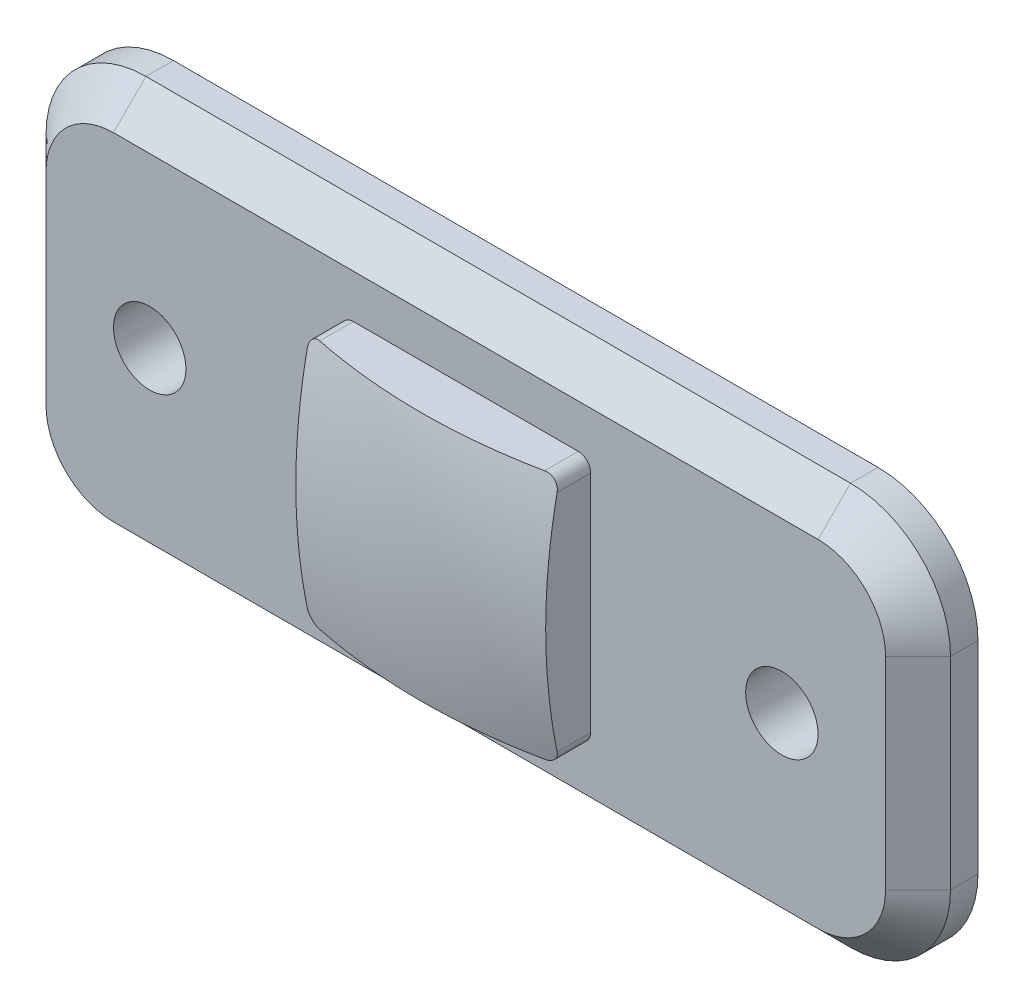
SolidWorks part; units mm, degrees
ref_plane "Ön Düzlem" through (0, 0, 0) normal (0, 0, 1) x (1, 0, 0)
ref_plane "Üst Düzlem" through (0, 0, 0) normal (0, 1, 0) x (1, 0, 0)
ref_plane "Sağ Düzlem" through (0, 0, 0) normal (1, 0, 0) x (0, 0, -1)
sketch "Çizim1" plane through (0, 0, 0) normal (0, 0, 1) x (1, 0, 0)
  line L0 (0, 0) -> (-12.65, 0) construction
  line L1 (-14.1, 8.045) -> (14.1, 8.045)
  line L2 (-18.1, 4.045) -> (-18.1, -4.045)
  line L3 (-14.1, -8.045) -> (14.1, -8.045)
  line L4 (18.1, 4.045) -> (18.1, -4.045)
  line L5 (-18.1, 8.045) -> (18.1, -8.045) construction
  line L6 (-18.1, -8.045) -> (18.1, 8.045) construction
  line L7 (0, 0) -> (0, 2.591) construction
  circle A0 centre (-12.65, 0) radius 1.45
  circle A1 centre (12.65, 0) radius 1.45
  arc A2 (-18.1, -4.045) -> (-14.1, -8.045) centre (-14.1, -4.045) ccw
  arc A3 (14.1, -8.045) -> (18.1, -4.045) centre (14.1, -4.045) ccw
  arc A4 (14.1, 8.045) -> (18.1, 4.045) centre (14.1, 4.045) cw
  arc A5 (-14.1, 8.045) -> (-18.1, 4.045) centre (-14.1, 4.045) ccw
  point P0 (0, 0)
  dimension "D3" = 2.9
  dimension "D5" = 4
  dimension "D1" = 36.2
  dimension "D2" = 16.09
  dimension "D4" = 12.65
extrude "Yükseklik-Ekstrüzyon1" add sketch "Çizim1" along normal blind 2.4
sketch "Çizim2" plane through (0, 0, 2.4) normal (0, 0, 1) x (1, 0, 0)
  line L1 (-4.5, 5) -> (4.5, 5)
  line L2 (-5, 4.5) -> (-5, -4.5)
  line L3 (-4.5, -5) -> (4.5, -5)
  line L4 (5, 4.5) -> (5, -4.5)
  line L5 (-5, 5) -> (5, -5) construction
  line L6 (-5, -5) -> (5, 5) construction
  arc A0 (4.5, 5) -> (5, 4.5) centre (4.5, 4.5) cw
  arc A1 (-5, -4.5) -> (-4.5, -5) centre (-4.5, -4.5) ccw
  arc A2 (-4.5, 5) -> (-5, 4.5) centre (-4.5, 4.5) ccw
  arc A3 (4.5, -5) -> (5, -4.5) centre (4.5, -4.5) ccw
  point P0 (0, 0)
  dimension "D3" = 0.5
  dimension "D1" = 10
  dimension "D2" = 10
extrude "Yükseklik-Ekstrüzyon2" add sketch "Çizim2" along normal blind 2.35
sketch "Çizim3" plane through (0, 0, 0) normal (0, 1, 0) x (1, 0, 0)
  line L0 (4.5, -4.75) -> (-4.5, -4.75) construction
  line L1 (5, -2.4) -> (5, -4.2) construction
  line L2 (5, -4.75) -> (5, -2.4) construction
  line L3 (0, -8.1331) -> (0, 3.765) construction
  line L5 (0, -8.1331) -> (11.1811, -8.7149)
  line L6 (11.1811, -8.7149) -> (7.9798, -3.3215)
  line L7 (3.765, 0) -> (5.9765, 3.0847)
  line L8 (5.9765, 3.0847) -> (3.765, 3.765)
  line L9 (3.765, 3.765) -> (0, 3.765)
  line L12 (0, 3.765) -> (0, -3.765)
  line L13 (0, -4.75) -> (0, -8.1331)
  line L14 (0, 0) -> (0, -2.184) construction
  arc A0 (0, -3.765) -> (3.765, 0) centre (0, 0) ccw
  arc A1 (0, -4.75) -> (7.9798, -3.3215) centre (0, 18.2523) ccw
  point P1 (7.9798, -3.3215)
  dimension "D1" = 7.53
  dimension "D2" = 1.8
revolve "Kes-Döndür1" cut sketch "Çizim3" angle 360 about L3
chamfer "Pah1" distance 1.3 angle 45 8 edges at (-16.9284, -6.8734, 2.4) (-18.1, 0, 2.4) (-16.9284, 6.8734, 2.4) (0, 8.045, 2.4) (16.9284, 6.8734, 2.4) (18.1, 0, 2.4) (16.9284, -6.8734, 2.4) (0, -8.045, 2.4)
fillet "Radyus1" radius 2.5 1 edges at (3.765, 0, 0)
